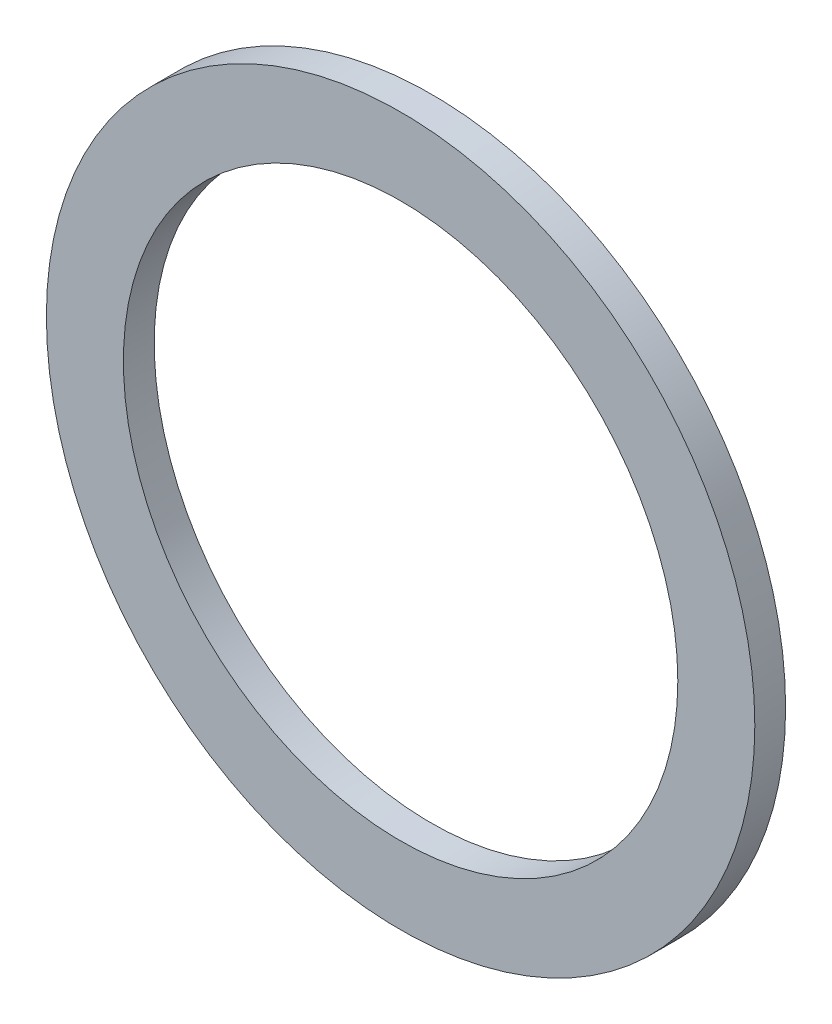
SolidWorks part; units mm, degrees
ref_plane "Front Plane" through (0, 0, 0) normal (0, 0, 1) x (1, 0, 0)
ref_plane "Top Plane" through (0, 0, 0) normal (0, 1, 0) x (1, 0, 0)
ref_plane "Right Plane" through (0, 0, 0) normal (1, 0, 0) x (0, 0, -1)
sketch "Sketch1" plane through (0, 0, 0) normal (0, 0, 1) x (1, 0, 0)
  circle A0 centre (0, 0) radius 115
  circle A1 centre (0, 0) radius 90
  dimension "D1" = 230
  dimension "D2" = 180
extrude "Boss-Extrude1" add sketch "Sketch1" along normal mid plane 10
